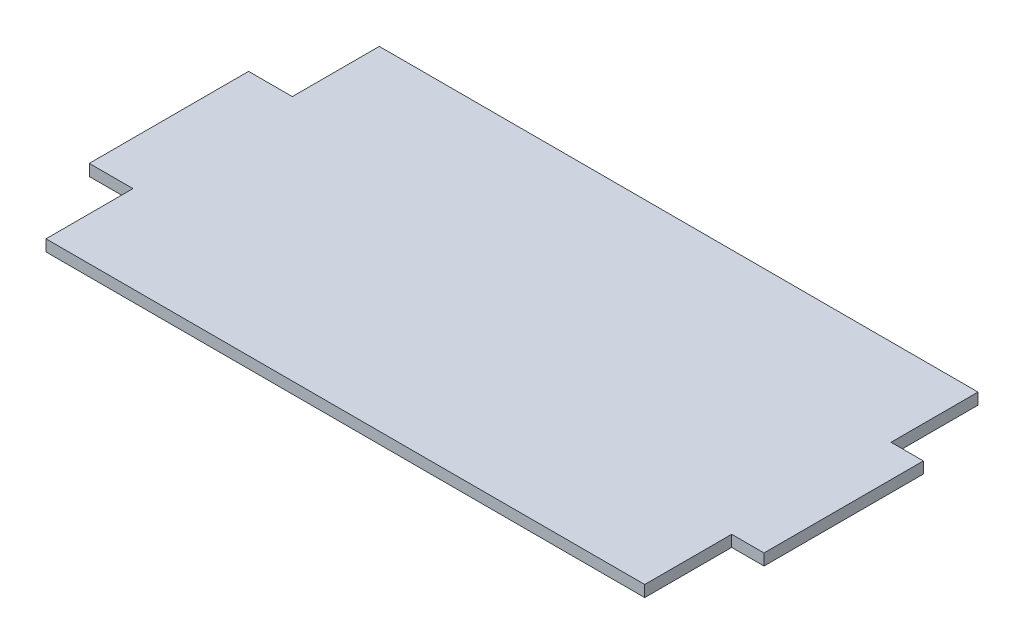
SolidWorks part; units mm, degrees
ref_plane "Ebene vorne" through (0, 0, 0) normal (1, 0, 0) x (0, 1, 0)
ref_plane "Ebene oben" through (0, 0, 0) normal (0, 0, 1) x (0, 1, 0)
ref_plane "Ebene rechts" through (0, 0, 0) normal (0, 1, 0) x (-1, 0, 0)
sketch "Skizze1" plane through (0, 15, 0) normal (0, 1, 0) x (1, 0, 0)
  line L6 (130, 73.2) -> (-130, 73.2) construction
  line L7 (-129, 73.2) -> (134, 73.2)
  line L8 (-129, 73.2) -> (-129, -73.2)
  line L9 (-129, -73.2) -> (134, -73.2)
  line L10 (134, 73.2) -> (134, -73.2)
  line L11 (-130, -73.2) -> (130, -73.2) construction
  line L12 (135, -60) -> (135, 60) construction
  line L13 (-130, 55) -> (-130, -55) construction
  line L14 (-148.2, 60) -> (-148.2, -60) construction
  line L15 (134, -35) -> (148.2, -35)
  line L16 (134, -35) -> (134, 35)
  line L17 (134, 35) -> (148.2, 35)
  line L18 (148.2, -35) -> (148.2, 35)
  line L19 (-129, 35) -> (-148.2, 35)
  line L20 (-129, 35) -> (-129, -35)
  line L21 (-129, -35) -> (-148.2, -35)
  line L22 (-148.2, 35) -> (-148.2, -35)
  line L23 (148.2, -55) -> (148.2, 55) construction
  line L24 (-136.8, 60) -> (-148.2, 60) construction
  point P25 (-129, 0)
  dimension "D1" = 1
  dimension "D2" = 1
  dimension "D3" = 25
extrude "Aufsatz-Linear austragen1" add sketch "Skizze1" along normal blind 5
other "Fläche löschen2" [suppressed]
